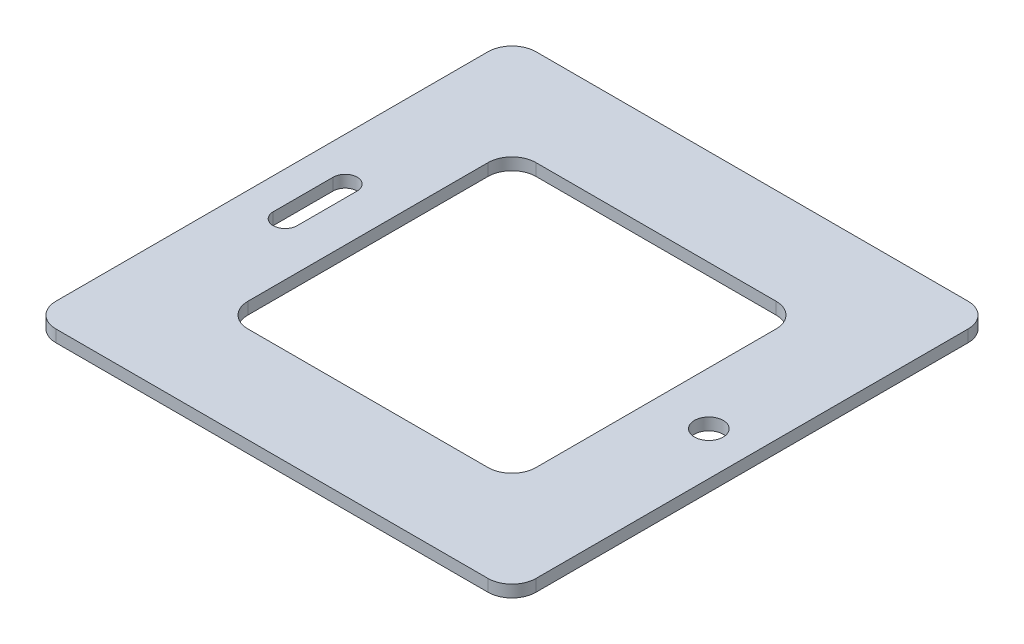
SolidWorks part; units mm, degrees
ref_plane "Front Plane" through (0, 0, 0) normal (0, 0, 1) x (1, 0, 0)
ref_plane "Top Plane" through (0, 0, 0) normal (0, 1, 0) x (1, 0, 0)
ref_plane "Right Plane" through (0, 0, 0) normal (1, 0, 0) x (0, 0, -1)
sketch "Sketch1" plane through (0, 0, 0) normal (0, 1, 0) x (1, 0, 0)
  line L1 (-100, -100) -> (100, -100)
  line L2 (-100, -100) -> (-100, 100)
  line L3 (-100, 100) -> (100, 100)
  line L4 (100, -100) -> (100, 100)
  line L5 (-100, -100) -> (100, 100) construction
  line L6 (-100, 100) -> (100, -100) construction
  line L7 (-50, -60) -> (50, -60)
  line L8 (-60, -50) -> (-60, 50)
  line L9 (-50, 60) -> (50, 60)
  line L10 (60, -50) -> (60, 50)
  line L11 (-60, -60) -> (60, 60) construction
  line L12 (-60, 60) -> (60, -60) construction
  arc A0 (-50, -60) -> (-60, -50) centre (-50, -50) cw
  arc A1 (50, -60) -> (60, -50) centre (50, -50) ccw
  arc A2 (50, 60) -> (60, 50) centre (50, 50) cw
  arc A3 (-60, 50) -> (-50, 60) centre (-50, 50) cw
  point P0 (0, 0)
  point P6 (0, 0)
  dimension "D3" = 10
  dimension "D1" = 200
  dimension "D2" = 120
extrude "Boss-Extrude1" add sketch "Sketch1" along normal blind 5
sketch "Sketch2" plane through (0, 5, 0) normal (0, 1, 0) x (1, 0, 0)
  line L0 (100, -100) -> (100, 100) construction
  line L3 (-100, 100) -> (-100, -100) construction
  line L6 (-82, -12.5) -> (-82, 12.5) construction
  line L7 (-87, -12.5) -> (-87, 12.5)
  line L8 (-77, -12.5) -> (-77, 12.5)
  circle A0 centre (82, 0) radius 6
  arc A1 (-87, -12.5) -> (-77, -12.5) centre (-82, -12.5) ccw
  arc A2 (-77, 12.5) -> (-87, 12.5) centre (-82, 12.5) ccw
  point P16 (-82, 0)
  dimension "D1" = 12
  dimension "D3" = 5
  dimension "D5" = 18
  dimension "D2" = 25
  dimension "D4" = 18
extrude "Cut-Extrude1" cut sketch "Sketch2" against normal blind 12
fillet "Redondeo1" radius 10 4 edges at (-100, 2.5, -100) (-100, 2.5, 100) (100, 2.5, -100) (100, 2.5, 100)
